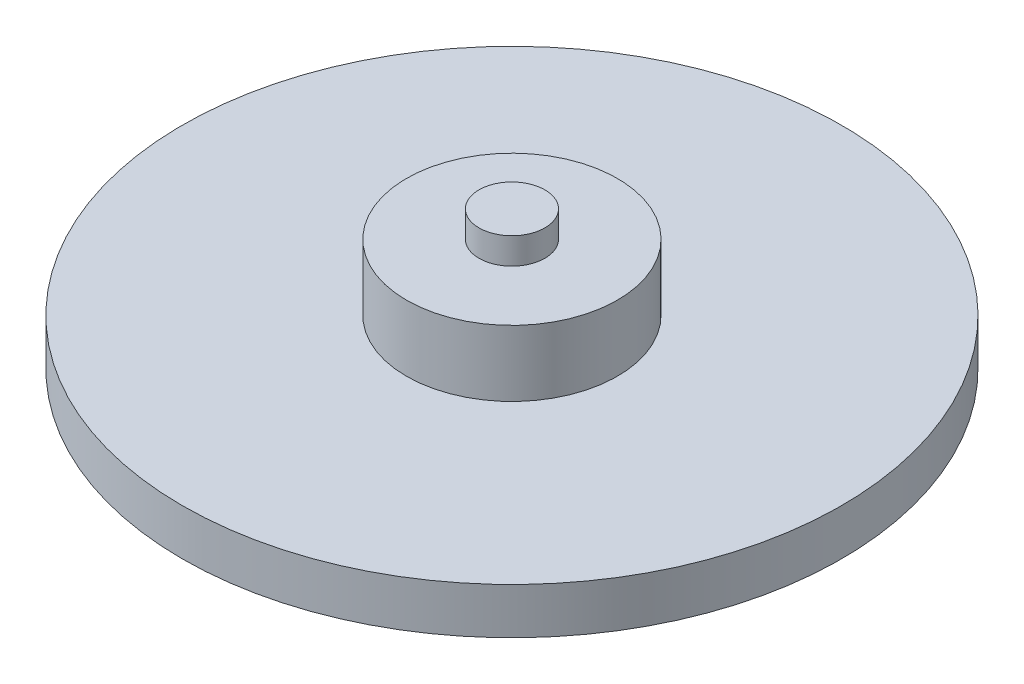
SolidWorks part; units mm, degrees
ref_plane "Front Plane" through (0, 0, 0) normal (0, 0, 1) x (1, 0, 0)
ref_plane "Top Plane" through (0, 0, 0) normal (0, 1, 0) x (1, 0, 0)
ref_plane "Right Plane" through (0, 0, 0) normal (1, 0, 0) x (0, 0, -1)
sketch "Sketch1" plane through (0, 0, 0) normal (0, 1, 0) x (1, 0, 0)
  circle A0 centre (0, 0) radius 25
  dimension "D1" = 50
extrude "Boss-Extrude1" add sketch "Sketch1" along normal blind 3.5
sketch "Sketch2" plane through (0, 3.5, 0) normal (0, 1, 0) x (1, 0, 0)
  circle A0 centre (0, 0) radius 8
  dimension "D1" = 16
extrude "Boss-Extrude2" add sketch "Sketch2" along normal blind 5
sketch "Sketch5" plane through (0, 8.5, 0) normal (0, 1, 0) x (1, 0, 0)
  circle A0 centre (0, 0) radius 2.5
  dimension "D1" = 5
extrude "Boss-Extrude3" add sketch "Sketch5" along normal blind 2
